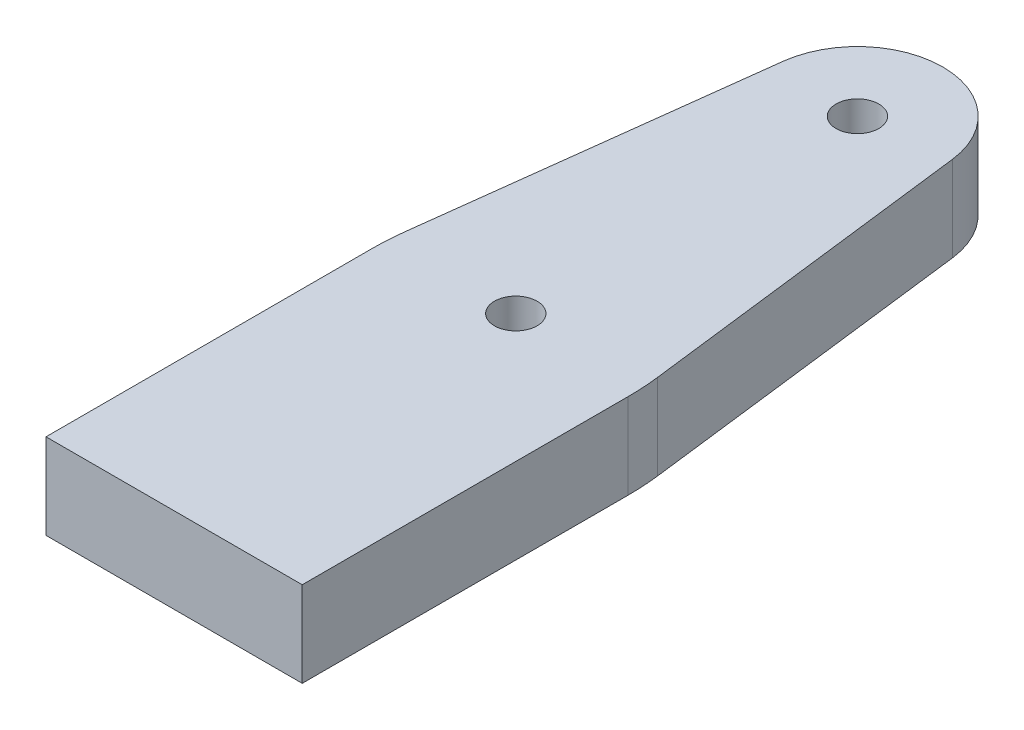
SolidWorks part; units mm, degrees
ref_plane "Front" through (0, 0, 0) normal (0, 0, 1) x (1, 0, 0)
ref_plane "Top" through (0, 0, 0) normal (0, 1, 0) x (1, 0, 0)
ref_plane "Right" through (0, 0, 0) normal (1, 0, 0) x (0, 0, -1)
sketch "Sketch1" plane through (0, 0, 0) normal (0, 1, 0) x (1, 0, 0)
  line L0 (-4.9625, 0.611) -> (-7.5, -20)
  line L1 (0, 0) -> (0, -36.3764) construction
  line L2 (7.5, -20) -> (4.9625, 0.611)
  line L3 (-7.5, -20) -> (-7.5, -40)
  line L4 (7.5, -20) -> (7.5, -40)
  line L5 (7.5, -40) -> (-7.5, -40)
  circle A0 centre (0, 0) radius 5
  dimension "D1" = 10
  dimension "D2" = 15
  dimension "D3" = 20
  dimension "D4" = 40
extrude "Boss-Extrude1" add sketch "Sketch1" along normal blind 5 contours A0 L0 L3 L5 L4 L2 | A0
fillet "Fillet1" radius 15 2 edges at (7.5, 2.5, 20) (-7.5, 2.5, 20)
sketch "Sketch2" plane through (0, 5, 0) normal (0, 1, 0) x (1, 0, 0)
  line L0 (0, 0) -> (0, -20) construction
  line L1 (-4.9625, 0.611) -> (4.9625, 0.611) construction
  circle A0 centre (0, 0) radius 1.25
  arc A1 (4.9625, 0.611) -> (-4.9625, 0.611) centre (0, 0) ccw construction
  circle A2 centre (0, -20) radius 1.25
  dimension "D1" = 2.5
  dimension "D2" = 2.5
  dimension "D3" = 20
extrude "Cut-Extrude1" cut sketch "Sketch2" against normal through all
